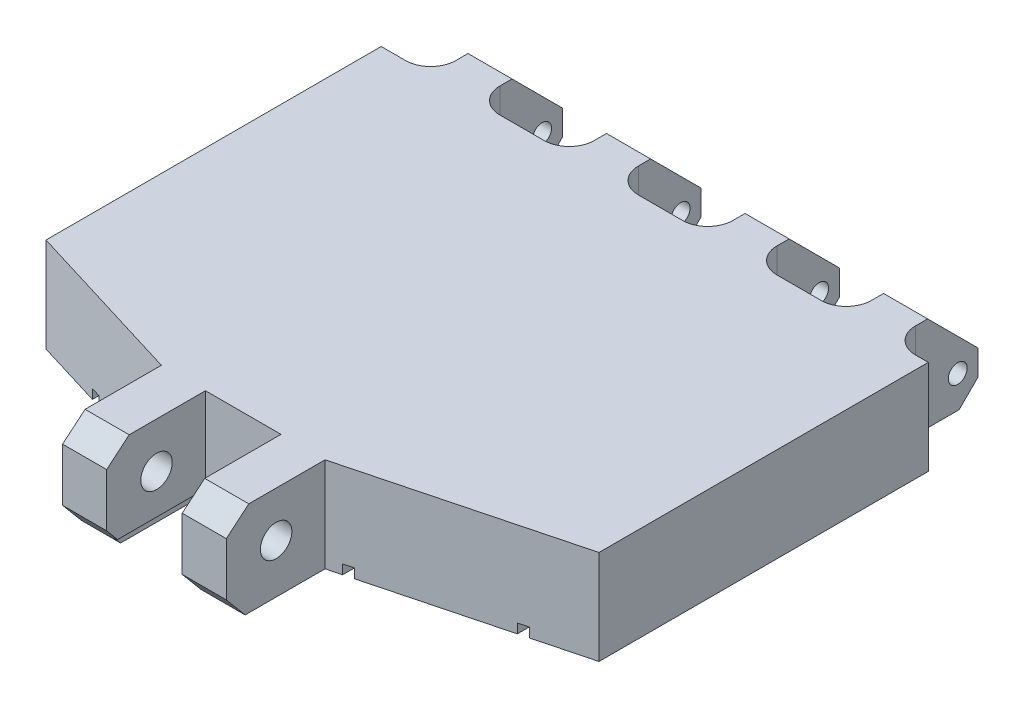
SolidWorks part; units mm, degrees
ref_plane "Спереди" through (0, 0, 0) normal (0, 0, 1) x (1, 0, 0)
ref_plane "Сверху" through (0, 0, 0) normal (0, 1, 0) x (1, 0, 0)
ref_plane "Справа" through (0, 0, 0) normal (1, 0, 0) x (0, 0, -1)
sketch "Эскиз1" plane through (0, 0, 0) normal (0, 1, 0) x (1, 0, 0)
  line L0 (37.9676, -30.6054) -> (37.9676, -7.8483) construction
  line L1 (1.1306, 58.9945) -> (19.8134, 58.9945) construction
  line L2 (15.9676, -24.6054) -> (15.9676, -4.1545) construction
  line L3 (-39.3913, -35) -> (47.5, -35)
  line L4 (-6.0324, -23.6054) -> (-6.0324, -5.9275) construction
  line L5 (-28.0324, -24.6054) -> (-28.0324, -9.3258) construction
  line L6 (-2.5324, 58.9945) -> (-9.5324, 58.9945)
  line L7 (-2.5324, 58.9945) -> (-2.5324, 41.9945)
  line L9 (19.4676, 58.9945) -> (12.4676, 58.9945)
  line L10 (19.4676, 58.9945) -> (19.4676, 41.9945)
  line L12 (12.4676, 58.9945) -> (12.4676, 41.9945)
  line L13 (-9.5324, 58.9945) -> (-9.5324, 41.9945)
  line L14 (-24.5324, 58.9945) -> (-24.5324, 41.9945)
  line L16 (-31.5324, 58.9945) -> (-31.5324, 41.9945)
  line L17 (-31.5324, 58.9945) -> (-24.5324, 58.9945)
  line L18 (41.4676, 58.9945) -> (41.4676, 41.9945)
  line L20 (34.4676, 58.9945) -> (34.4676, 41.9945)
  line L21 (34.4676, 58.9945) -> (41.4676, 58.9945)
  line L22 (41.4676, 41.9945) -> (47.5, 41.9945)
  line L23 (47.5, 41.9945) -> (47.5, -35)
  line L24 (34.4676, 41.9945) -> (19.4676, 41.9945)
  line L25 (-39.3913, 41.9945) -> (-39.3913, -35)
  line L26 (12.4676, 41.9945) -> (-2.5324, 41.9945)
  line L27 (-9.5324, 41.9945) -> (-24.5324, 41.9945)
  line L28 (-31.5324, 41.9945) -> (-39.3913, 41.9945)
extrude "Вытянуть1" add sketch "Эскиз1" along normal blind 15
sketch "Эскиз2" plane through (0, 15, 0) normal (0, 1, 0) x (1, 0, 0)
  line L0 (0, -55.0916) -> (0, -66.0354) construction
  line L1 (-39.3913, -35) -> (47.5, -35) construction
  line L2 (-14.9566, -19.3096) -> (-5.8788, -19.3096) construction
  line L5 (6, -50.6904) -> (-6, -50.6904)
  line L6 (6, -50.6904) -> (6, -19.3096)
  line L7 (6, -19.3096) -> (-6, -19.3096)
  line L8 (-40.2823, -10.9683) -> (-13, -19.3096)
  line L9 (-6, -50.6904) -> (-6, -19.3096)
  line L10 (-13, -19.3096) -> (-13, -35)
  line L11 (-40.2823, -10.9683) -> (-40.2823, -35)
  line L12 (-40.2823, -35) -> (-13, -35)
  line L13 (6, -50.6904) -> (-6, -19.3096) construction
  line L14 (49.5758, -35) -> (13, -35)
  line L15 (49.5758, -9.7641) -> (49.5758, -35)
  line L16 (13, -19.3096) -> (13, -35)
  line L17 (49.5758, -9.7641) -> (13, -19.3096)
  line L18 (6, -19.3096) -> (-6, -50.6904) construction
  point P2 (0, -35)
  dimension "D1" = 7
  dimension "D2" = 7
extrude "Вытянуть2" cut sketch "Эскиз2" against normal through all
chamfer "Фаска1" distance 3 angle 50 4 edges at (-9.5, 0, 35) (9.5, 0, 35) (-9.5, 15, 35) (9.5, 15, 35)
sketch "Эскиз4" plane through (-13, 0, 0) normal (-1, 0, 0) x (0, 0, 1)
  line L0 (35, 7.7876) -> (46.6109, 7.7876) construction
  circle A0 centre (27.0802, 7.7876) radius 2.5
extrude "Вытянуть3" cut sketch "Эскиз4" against normal through all
sketch "Эскиз8" plane through (-31.5324, 0, 0) normal (-1, 0, 0) x (0, 0, 1)
  line L0 (-36.4793, 5.0999) -> (-71.2976, 5.0999) construction
  circle A0 centre (-52.6958, 5.0999) radius 1.5
extrude "Вырез-Вытянуть3" cut sketch "Эскиз8" against normal through all
sketch "Эскиз9" plane through (-31.5324, 0, 0) normal (-1, 0, 0) x (0, 0, 1)
  line L0 (-47.922, 15) -> (-55.9218, 7.0002)
  line L1 (-55.9218, 7.0002) -> (-55.9218, 3.0002)
  line L2 (-55.9218, 3.0002) -> (-52.9216, 0)
  line L3 (-47.922, 15) -> (-58.9945, 15)
  line L4 (-58.9945, 15) -> (-58.9945, 0)
  line L5 (-58.9945, 0) -> (-52.9216, 0)
  line L6 (-58.9945, 15) -> (-58.9945, 0) construction
extrude "Вырез-Вытянуть4" cut sketch "Эскиз9" against normal through all
sketch "Эскиз11" plane through (0, 0, 0) normal (0, -1, 0) x (1, 0, 0)
  line L0 (37.9676, 30.6054) -> (37.9676, 1.5321) construction
  line L1 (15.9676, 30.6054) -> (15.9676, 13.8513) construction
  line L2 (-6.0324, 30.6054) -> (-6.0324, 7.4052) construction
  line L3 (-28.0324, 30.6054) -> (-28.0324, 16.1433) construction
  line L4 (-6.7824, -46.7423) -> (-5.2824, 37.2007) construction
  line L5 (38.7176, 37.2007) -> (37.2176, 37.2007)
  line L6 (38.7176, 37.2007) -> (38.7176, -46.7423)
  line L7 (38.7176, -46.7423) -> (37.2176, -46.7423)
  line L8 (37.2176, 37.2007) -> (37.2176, -46.7423)
  line L9 (38.7176, 37.2007) -> (37.2176, -46.7423) construction
  line L10 (38.7176, -46.7423) -> (37.2176, 37.2007) construction
  line L11 (-6.7824, 37.2007) -> (-5.2824, -46.7423) construction
  line L12 (-5.2824, 37.2007) -> (-5.2824, -46.7423)
  line L13 (-6.7824, -46.7423) -> (-5.2824, -46.7423)
  line L14 (-6.7824, 37.2007) -> (-6.7824, -46.7423)
  line L15 (-6.7824, 37.2007) -> (-5.2824, 37.2007)
  line L16 (-28.7824, -46.7423) -> (-27.2824, 43.7197) construction
  line L17 (16.7176, 43.7197) -> (15.2176, 43.7197)
  line L18 (16.7176, 43.7197) -> (16.7176, -46.7423)
  line L19 (16.7176, -46.7423) -> (15.2176, -46.7423)
  line L20 (15.2176, 43.7197) -> (15.2176, -46.7423)
  line L21 (16.7176, 43.7197) -> (15.2176, -46.7423) construction
  line L22 (16.7176, -46.7423) -> (15.2176, 43.7197) construction
  line L23 (-28.7824, 43.7197) -> (-27.2824, -46.7423) construction
  line L24 (-27.2824, 43.7197) -> (-27.2824, -46.7423)
  line L25 (-28.7824, -46.7423) -> (-27.2824, -46.7423)
  line L26 (-28.7824, 43.7197) -> (-28.7824, -46.7423)
  line L27 (-28.7824, 43.7197) -> (-27.2824, 43.7197)
  point P7 (37.9676, -4.7708)
  point P17 (-6.0324, -4.7708)
  point P18 (15.9676, -1.5113)
  point P27 (-28.0324, -1.5113)
extrude "Вырез-Вытянуть6" cut sketch "Эскиз11" against normal blind 1.5
fillet "Скругление7" radius 4 8 edges at (41.4676, 7.5, -41.9945) (34.4676, 7.5, -41.9945) (19.4676, 7.5, -41.9945) (12.4676, 7.5, -41.9945) (-2.5324, 7.5, -41.9945) (-9.5324, 7.5, -41.9945) (-24.5324, 7.5, -41.9945) (-31.5324, 7.5, -41.9945)
